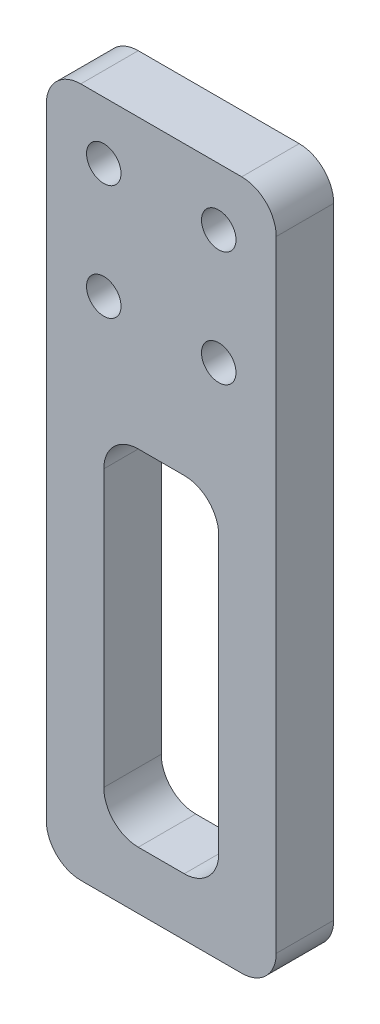
SolidWorks part; units mm, degrees
material "Thornel Mat VMA"
ref_plane "前视基准面" through (0, 0, 0) normal (0, 0, 1) x (1, 0, 0)
ref_plane "上视基准面" through (0, 0, 0) normal (0, 1, 0) x (1, 0, 0)
ref_plane "右视基准面" through (0, 0, 0) normal (1, 0, 0) x (0, 0, -1)
sketch "草图1" plane through (0, 0, 0) normal (0, 0, 1) x (1, 0, 0)
  line L1 (-10, -30) -> (10, -30)
  line L2 (-10, -30) -> (-10, 30)
  line L3 (-10, 30) -> (10, 30)
  line L4 (10, -30) -> (10, 30)
  line L5 (-10, -30) -> (10, 30) construction
  line L6 (-10, 30) -> (10, -30) construction
  point P0 (0, 0)
  dimension "D1" = 20
  dimension "D2" = 60
extrude "凸台-拉伸1" add sketch "草图1" along normal blind 5
sketch "草图2" plane through (0, 0, 5) normal (0, 0, 1) x (1, 0, 0)
  line L0 (0, 30) -> (0, -30) construction
  line L1 (10, 30) -> (-10, 30) construction
  line L2 (-10, -30) -> (10, -30) construction
  line L4 (-5, 15) -> (5, 15) construction
  line L5 (-5, 15) -> (-5, 25) construction
  line L6 (-5, 25) -> (5, 25) construction
  line L7 (5, 15) -> (5, 25) construction
  line L8 (-5, 15) -> (5, 25) construction
  line L9 (-5, 25) -> (5, 15) construction
  circle A0 centre (-5, 25) radius 1.5
  circle A1 centre (-5, 15) radius 1.5
  circle A2 centre (5, 15) radius 1.5
  circle A3 centre (5, 25) radius 1.5
  point P6 (0, 20)
  dimension "D4" = 3
  dimension "D5" = 3
  dimension "D1" = 10
  dimension "D2" = 10
  dimension "D3" = 10
extrude "切除-拉伸1" cut sketch "草图2" against normal through all
sketch "草图3" plane through (0, 0, 5) normal (0, 0, 1) x (1, 0, 0)
  line L0 (0, -30) -> (0, 30) construction
  line L1 (-10, -30) -> (10, -30) construction
  line L2 (10, 30) -> (-10, 30) construction
  line L4 (-5, -25) -> (5, -25)
  line L5 (-5, -25) -> (-5, 5)
  line L6 (-5, 5) -> (5, 5)
  line L7 (5, -25) -> (5, 5)
  line L8 (-5, -25) -> (5, 5) construction
  line L9 (-5, 5) -> (5, -25) construction
  point P6 (0, -10)
  dimension "D1" = 30
  dimension "D2" = 20
  dimension "D3" = 10
extrude "切除-拉伸2" cut sketch "草图3" against normal through all
fillet "圆角1" radius 3 8 edges at (-10, 30, 2.5) (10, 30, 2.5) (10, -30, 2.5) (-10, -30, 2.5) (5, -25, 2.5) (-5, -25, 2.5) (5, 5, 2.5) (-5, 5, 2.5)
